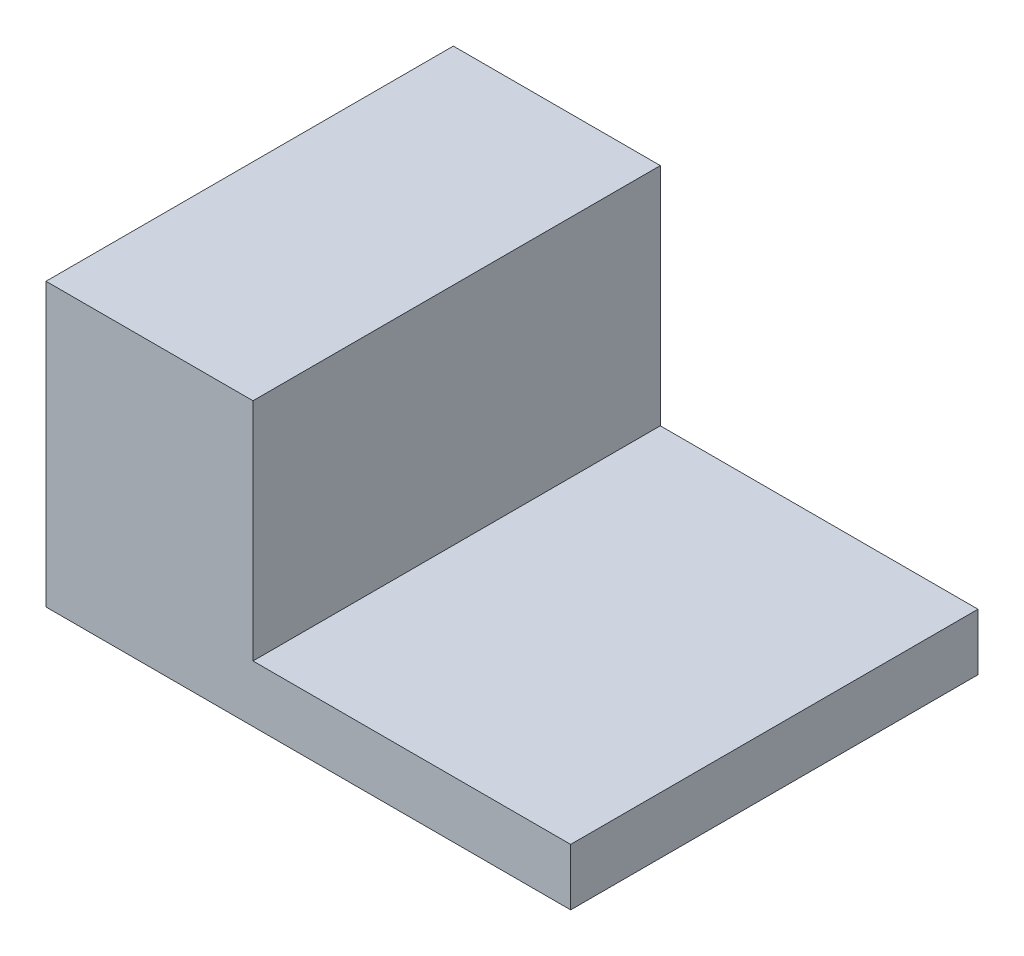
SolidWorks part; units mm, degrees
ref_plane "Front Plane" through (0, 0, 0) normal (0, 0, 1) x (1, 0, 0)
ref_plane "Top Plane" through (0, 0, 0) normal (0, 1, 0) x (1, 0, 0)
ref_plane "Right Plane" through (0, 0, 0) normal (1, 0, 0) x (0, 0, -1)
sketch "Sketch2" plane through (0, 0, 0) normal (0, 0, 1) x (1, 0, 0)
  line L0 (0, 35.1845) -> (0, 0)
  line L1 (0, 0) -> (65.4324, 0)
  line L2 (65.4324, 0) -> (65.4324, 7.0788)
  line L3 (65.4324, 7.0788) -> (25.8134, 7.0788)
  line L4 (25.8134, 7.0788) -> (25.8134, 35.1845)
  line L5 (25.8134, 35.1845) -> (0, 35.1845)
extrude "Extrude2" add sketch "Sketch2" along normal blind 50.8
